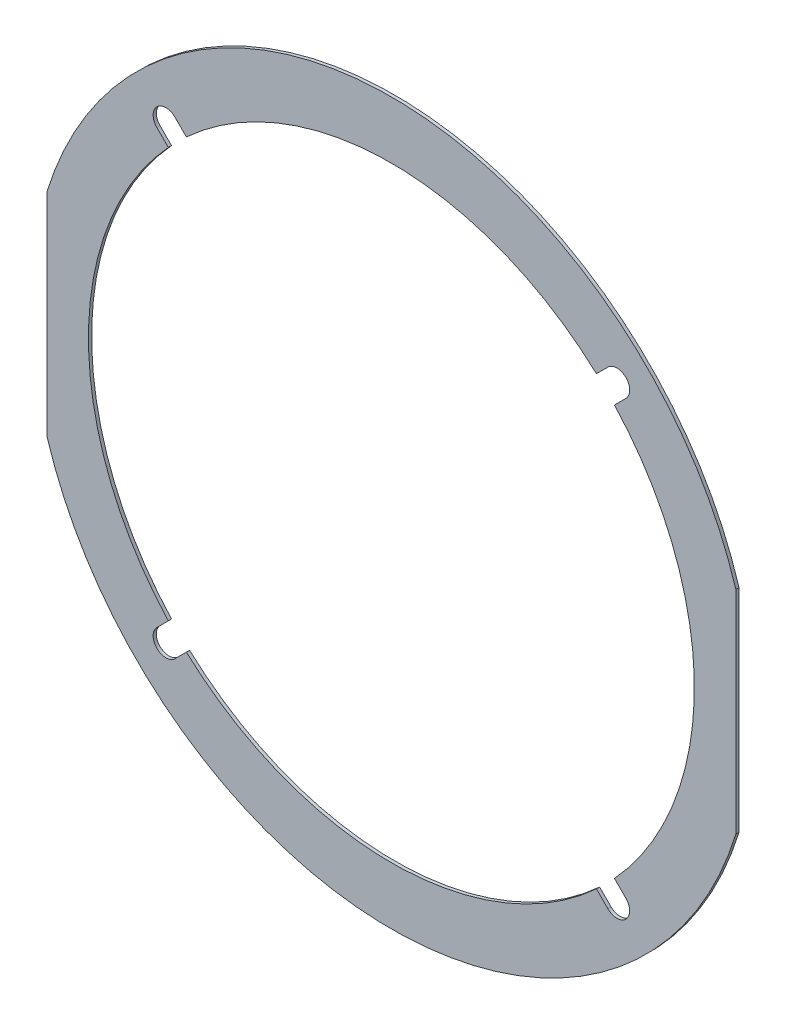
SolidWorks part; units mm, degrees
ref_plane "Front Plane" through (0, 0, 0) normal (0, 0, 1) x (1, 0, 0)
ref_plane "Top Plane" through (0, 0, 0) normal (0, 1, 0) x (1, 0, 0)
ref_plane "Right Plane" through (0, 0, 0) normal (1, 0, 0) x (0, 0, -1)
sketch "Sketch1" plane through (0, 0, 0) normal (0, 0, 1) x (-1, 0, 0)
  line L0 (17.486, 16.0718) -> (18.3848, 16.9706)
  line L1 (16.0718, 17.486) -> (16.9706, 18.3848)
  line L2 (0, 0) -> (19.9758, 19.9758) construction
  line L3 (16.0718, -17.486) -> (16.9706, -18.3848)
  line L4 (-27, 8.3104) -> (-27, -8.3104)
  line L5 (27, -8.3104) -> (27, 8.3104)
  line L6 (17.486, -16.0718) -> (18.3848, -16.9706)
  line L7 (-17.486, -16.0718) -> (-18.3848, -16.9706)
  line L8 (-16.0718, -17.486) -> (-16.9706, -18.3848)
  line L9 (-16.0718, 17.486) -> (-16.9706, 18.3848)
  line L10 (-17.486, 16.0718) -> (-18.3848, 16.9706)
  arc A0 (16.9706, 18.3848) -> (18.3848, 16.9706) centre (17.6777, 17.6777) cw
  arc A1 (18.3848, -16.9706) -> (16.9706, -18.3848) centre (17.6777, -17.6777) cw
  arc A2 (-16.9706, -18.3848) -> (-18.3848, -16.9706) centre (-17.6777, -17.6777) cw
  arc A3 (-18.3848, 16.9706) -> (-16.9706, 18.3848) centre (-17.6777, 17.6777) cw
  arc A4 (-27, -8.3104) -> (27, -8.3104) centre (0, 0) ccw
  arc A5 (27, 8.3104) -> (-27, 8.3104) centre (0, 0) ccw
  circle A8 centre (-17.6777, -17.6777) radius 1 construction
  circle A9 centre (17.6777, -17.6777) radius 1 construction
  circle A10 centre (17.6777, 17.6777) radius 1 construction
  circle A11 centre (-17.6777, 17.6777) radius 1 construction
  circle A13 centre (0, 0) radius 23.75
  dimension "D2" = 2
  dimension "D1" = 47.5
  dimension "D3" = 28.25
  dimension "D4" = 17.6777
  dimension "D5" = 27
  dimension "D6" = 17.6777
  dimension "D7" = 17.6777
  dimension "D8" = 17.6777
  dimension "D9" = 4
extrude "Boss-Extrude2" add sketch "Sketch1" along normal blind 0.25 contours L5 A5 L4 A4 A13 L8 A2 L7 L10 A3 L9 L1 A0 L0 L6 A1 L3
